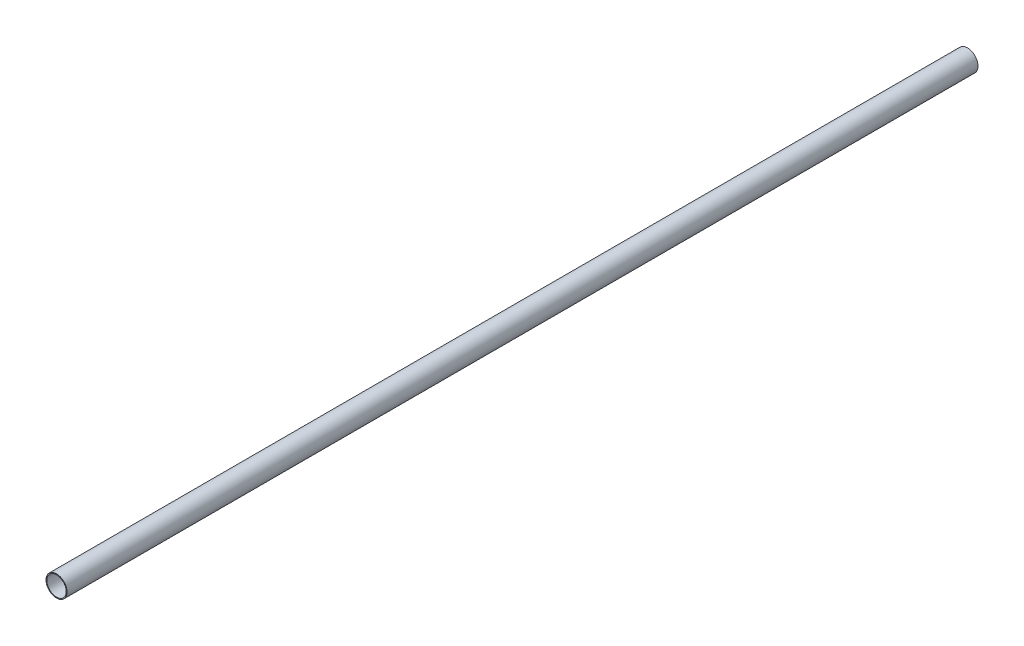
SolidWorks part; units mm, degrees
material "Thornel Mat VMA"
ref_plane "Front" through (0, 0, 0) normal (0, 0, 1) x (1, 0, 0)
ref_plane "Top" through (0, 0, 0) normal (0, 1, 0) x (1, 0, 0)
ref_plane "Right" through (0, 0, 0) normal (1, 0, 0) x (0, 0, -1)
sketch "Sketch1" plane through (0, 0, 0) normal (0, 0, 1) x (1, 0, 0)
  circle A0 centre (0, 0) radius 12.5603
  circle A1 centre (0, 0) radius 11.5443
  dimension "D1" = 25.1206
  dimension "D2" = 1.016
extrude "Boss-Extrude1" add sketch "Sketch1" along normal blind 1085.85
sketch "Sketch2" plane through (0, 0, 0) normal (0, 1, 0) x (1, 0, 0)
  line L0 (12.5603, 0) -> (13.8176, -1016) construction
  line L1 (13.8176, -1016) -> (12.5603, -1016) construction
  line L2 (12.5603, -1085.85) -> (12.5603, 0) construction
  line L3 (0, -1085.85) -> (0, 0) construction
  line L4 (12.5603, 0) -> (12.5603, -1016) construction
  dimension "D1" = 1016
  dimension "D2" = 13.8176
  dimension "D3" = 179.929
ref_plane "Plane1" through (0, 0, 1085.85) normal (0, 0, 1) x (1, 0, 0)
